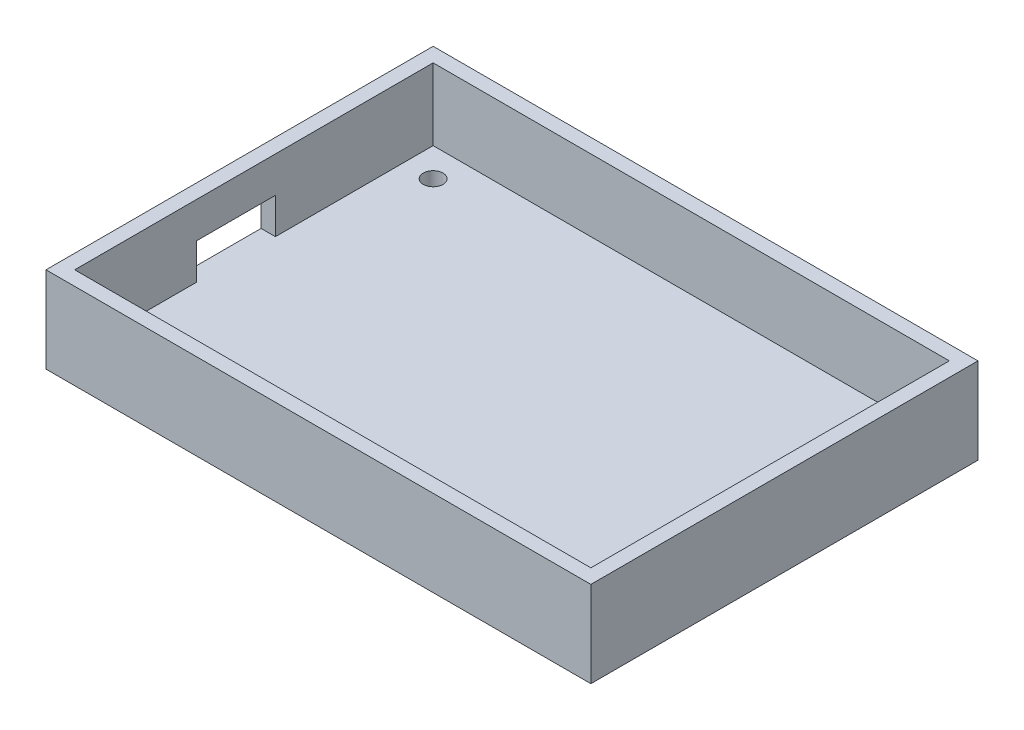
SolidWorks part; units mm, degrees
ref_plane "Front Plane" through (0, 0, 0) normal (0, 0, 1) x (1, 0, 0)
ref_plane "Top Plane" through (0, 0, 0) normal (0, 1, 0) x (1, 0, 0)
ref_plane "Right Plane" through (0, 0, 0) normal (1, 0, 0) x (0, 0, -1)
sketch "Sketch1" plane through (0, 0, 0) normal (0, 1, 0) x (1, 0, 0)
  line L5 (-45.72, -31.75) -> (45.72, 31.75) construction
  line L6 (-45.72, 31.75) -> (45.72, -31.75) construction
  line L7 (-48.26, -34.29) -> (48.26, -34.29)
  line L8 (-48.26, -34.29) -> (-48.26, 34.29)
  line L9 (-48.26, 34.29) -> (48.26, 34.29)
  line L10 (48.26, -34.29) -> (48.26, 34.29)
  line L11 (-48.26, -34.29) -> (48.26, 34.29) construction
  line L12 (-48.26, 34.29) -> (48.26, -34.29) construction
  point P0 (0, 0)
  point P6 (0, 0)
extrude "Boss-Extrude2" add sketch "Sketch1" along normal blind 2.54
sketch "Sketch4" plane through (0, 2.54, 0) normal (0, 1, 0) x (1, 0, 0)
  line L0 (45.72, -31.75) -> (45.72, 31.75)
  line L1 (45.72, 31.75) -> (-45.72, 31.75)
  line L2 (-45.72, 31.75) -> (-45.72, -31.75)
  line L3 (-45.72, -31.75) -> (45.72, -31.75)
  line L4 (48.26, -34.29) -> (48.26, 34.29)
  line L5 (48.26, 34.29) -> (-48.26, 34.29)
  line L6 (-48.26, 34.29) -> (-48.26, -34.29)
  line L7 (-48.26, -34.29) -> (48.26, -34.29)
  line L8 (48.26, -34.29) -> (48.26, 34.29)
  line L9 (48.26, 34.29) -> (-48.26, 34.29)
  line L10 (-48.26, 34.29) -> (-48.26, -34.29)
  line L11 (-48.26, -34.29) -> (48.26, -34.29)
  dimension "D1" = 0
  dimension "D2" = 2.54
extrude "Boss-Extrude3" add sketch "Sketch4" along normal blind 12.7
sketch "Sketch5" plane through (-48.26, 0, 0) normal (-1, 0, 0) x (0, 0, 1)
  line L0 (-34.29, 15.24) -> (-34.29, 0) construction
  line L1 (-3.81, 8.89) -> (10.16, 8.89)
  line L2 (-3.81, 8.89) -> (-3.81, 2.54)
  line L3 (-3.81, 2.54) -> (10.16, 2.54)
  line L4 (10.16, 8.89) -> (10.16, 2.54)
  line L5 (-3.81, 8.89) -> (10.16, 2.54) construction
  line L6 (-3.81, 2.54) -> (10.16, 8.89) construction
  line L7 (34.29, 15.24) -> (34.29, 0) construction
  line L8 (-34.29, 0) -> (34.29, 0) construction
  point P0 (3.175, 5.715)
  dimension "D1" = 30.48
  dimension "D2" = 24.13
  dimension "D3" = 2.54
  dimension "D4" = 6.35
extrude "Cut-Extrude2" cut sketch "Sketch5" against normal blind 12.7
sketch "Sketch6" plane through (0, 2.54, 0) normal (0, 1, 0) x (1, 0, 0)
  line L0 (-45.72, 31.75) -> (-45.72, -31.75) construction
  line L1 (45.72, 31.75) -> (-45.72, 31.75) construction
  line L2 (45.72, 31.75) -> (-45.72, 31.75) construction
  circle A0 centre (-40.64, 26.67) radius 1.75
  circle A1 centre (39.37, 26.416) radius 1.75
  circle A2 centre (39.37, -25.654) radius 1.75
  point P12 (0, 0)
  point P14 (0, 0)
  point P16 (0, 0)
  dimension "D1" = 5.08
  dimension "D3" = 3.5
  dimension "D2" = 5.08
  dimension "D4" = 5.334
  dimension "D5" = 80.01
  dimension "D6" = 52.07
extrude "Cut-Extrude4" cut sketch "Sketch6" against normal blind 2.54
